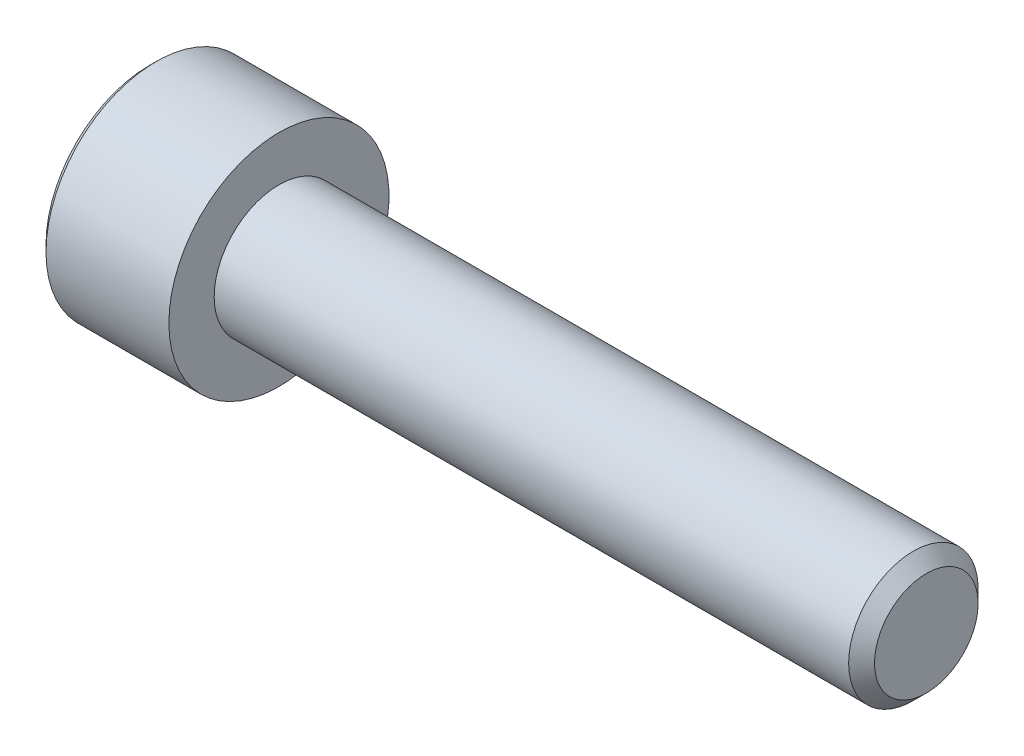
SolidWorks part; units mm, degrees
ref_plane "前视基准面" through (0, 0, 0) normal (0, 0, 1) x (1, 0, 0)
ref_plane "上视基准面" through (0, 0, 0) normal (0, 1, 0) x (1, 0, 0)
ref_plane "右视基准面" through (0, 0, 0) normal (1, 0, 0) x (0, 0, -1)
sketch "草图1" plane through (0, 0, 0) normal (0, 0, 1) x (1, 0, 0)
  line L0 (0, 0) -> (0, 2.5)
  line L1 (0, 2.5) -> (-25, 2.5)
  line L2 (-25, 2.5) -> (-25, 4.25)
  line L3 (-25, 4.25) -> (-30, 4.25)
  line L4 (-30, 4.25) -> (-30, 0)
  line L5 (-30, 0) -> (0, 0)
  line L6 (0, 0) -> (4.7488, 0) construction
  dimension "D1" = 5
  dimension "D2" = 25
  dimension "D3" = 5
  dimension "D4" = 8.5
revolve "旋转1" add sketch "草图1" angle 360 about L6
cosmetic thread "装饰螺纹线1" parameters "D1"=25, "D2"=4.3
chamfer "倒角1" distance 0.5 angle 45 1 edges at (0, 0, 2.5)
sketch "草图2" plane through (-30, 0, 0) normal (-1, 0, 0) x (0, 0, 1)
  line L1 (0, 2.3094) -> (-2, 1.1547)
  line L2 (-2, 1.1547) -> (-2, -1.1547)
  line L3 (-2, -1.1547) -> (0, -2.3094)
  line L4 (0, -2.3094) -> (2, -1.1547)
  line L5 (2, -1.1547) -> (2, 1.1547)
  line L6 (2, 1.1547) -> (0, 2.3094)
  circle A0 centre (0, 0) radius 2 construction
  dimension "D1" = 4
extrude "切除-拉伸1" cut sketch "草图2" against normal blind 2.5
chamfer "倒角2" distance 0.255 angle 45 1 edges at (-30, 0, 4.25)
sketch "草图4" plane through (-27.5, 0, 0) normal (-1, 0, 0) x (0, 0, 1)
  line L1 (0, -2.3094) -> (2, -1.1547)
  line L2 (2, -1.1547) -> (2, 1.1547)
  line L3 (2, 1.1547) -> (0, 2.3094)
  line L4 (0, 2.3094) -> (-2, 1.1547)
  line L5 (-2, 1.1547) -> (-2, -1.1547)
  line L6 (2, 1.1547) -> (0, 2.3094)
  line L7 (0, 2.3094) -> (-2, 1.1547)
  line L8 (-2, 1.1547) -> (-2, -1.1547)
  line L9 (-2, -1.1547) -> (0, -2.3094)
  line L10 (0, -2.3094) -> (2, -1.1547)
  line L11 (2, -1.1547) -> (2, 1.1547)
  line L12 (2, 1.1547) -> (0, 2.3094) construction
  line L13 (0, 2.3094) -> (-2, 1.1547) construction
  line L14 (-2, 1.1547) -> (-2, -1.1547) construction
  line L15 (-2, -1.1547) -> (0, -2.3094) construction
  line L16 (0, -2.3094) -> (2, -1.1547) construction
  line L17 (2, -1.1547) -> (2, 1.1547) construction
  line L18 (-2, -1.1547) -> (0, -2.3094)
  circle A0 centre (0, 0) radius 2 construction
  dimension "D1" = 0
extrude "切除-拉伸2" cut sketch "草图4" against normal through all draft 59
